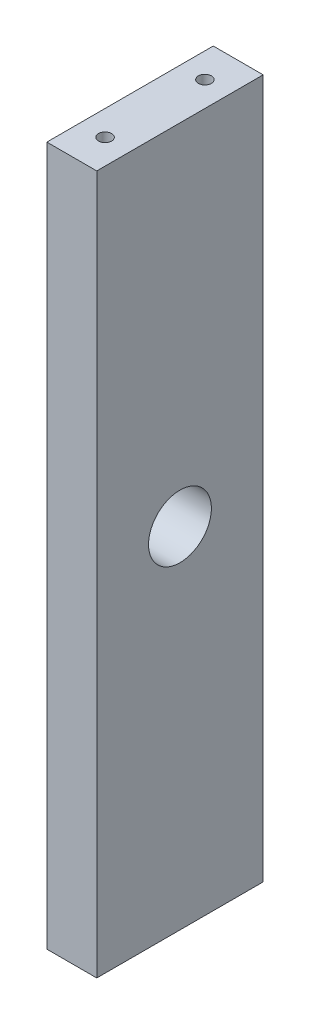
SolidWorks part; units mm, degrees
ref_plane "Front Plane" through (0, 0, 0) normal (0, 0, 1) x (1, 0, 0)
ref_plane "Top Plane" through (0, 0, 0) normal (0, 1, 0) x (1, 0, 0)
ref_plane "Right Plane" through (0, 0, 0) normal (1, 0, 0) x (0, 0, -1)
sketch "Sketch1" plane through (0, 0, 0) normal (1, 0, 0) x (0, 0, -1)
  line L1 (-15.875, -66.675) -> (15.875, -66.675)
  line L2 (-15.875, -66.675) -> (-15.875, 66.675)
  line L3 (-15.875, 66.675) -> (15.875, 66.675)
  line L4 (15.875, -66.675) -> (15.875, 66.675)
  line L5 (-15.875, -66.675) -> (15.875, 66.675) construction
  line L6 (-15.875, 66.675) -> (15.875, -66.675) construction
  point P0 (0, 0)
  dimension "D1" = 31.75
  dimension "D2" = 133.35
extrude "Boss-Extrude1" add sketch "Sketch1" along normal mid plane 9.525
sketch "Sketch2" plane through (0, 66.675, 0) normal (0, 1, 0) x (1, 0, 0)
  line L0 (0, 9.525) -> (0, -9.525) construction
  line L1 (-4.7625, 15.875) -> (-4.7625, -15.875) construction
  line L2 (4.7625, 15.875) -> (-4.7625, 15.875) construction
  point P2 (0, 0)
  point P5 (-4.7625, 0)
  point P8 (0, 15.875)
  point P10 (0, 9.525)
  point P11 (0, -9.525)
  dimension "D1" = 19.05
hole_wizard "M3x0.5 Tapped Hole1" positions "Sketch3" profile "Sketch4" tap size "M3x0.5" standard "ANSI Metric"
sketch "Sketch3" plane through (0, 66.675, 0) normal (0, 1, 0) x (1, 0, 0)
  point P0 (0, 9.525)
  point P3 (0, -9.525)
sketch "Sketch4" plane through (0, 66.675, -9.525) normal (1, 0, 0) x (0, 0, 1)
  line L0 (0, 0) -> (0, 13.4511)
  line L1 (0, 13.4511) -> (1.25, 12.7)
  line L2 (1.25, 12.7) -> (1.25, 0)
  line L5 (1.25, 0) -> (0, 0)
  line L10 (0, 13.4511) -> (-1.25, 12.7) construction
  line L11 (0, -6.35) -> (0, 107.95) construction
  dimension "Tap Drill Dia." = 2.5
  dimension "Tap Drill Depth" = 12.7
  dimension "Drill Angle" = 118
cosmetic thread "Hole Thread1" parameters "D1"=6.096, "D2"=3
cosmetic thread "Hole Thread2" parameters "D1"=6.096, "D2"=3
mirror "Mirror1" about plane through (0, 0, 0) normal (0, 1, 0) of "M3x0.5 Tapped Hole1"
cosmetic thread "Hole Thread3" parameters "D1"=6.096, "D2"=3
cosmetic thread "Hole Thread4" parameters "D1"=6.096, "D2"=3
sketch "Sketch5" plane through (4.7625, 0, 0) normal (1, 0, 0) x (0, 0, -1)
  point P0 (0, 0)
hole_wizard "Ø12.0mm Dowel Hole1" positions "Sketch6" profile "Sketch8" hole size "Ø12.0" standard "ANSI Metric" end condition through all
sketch "Sketch6" plane through (4.7625, 0, 0) normal (1, 0, 0) x (0, 0, -1)
  point P0 (0, 0)
sketch "Sketch8" plane through (4.7625, 0, 0) normal (0, 1, 0) x (0, 0, -1)
  line L0 (0, 0) -> (0, 9.525)
  line L1 (0, 9.525) -> (6, 9.525)
  line L2 (6, 9.525) -> (6, 0)
  line L5 (6, 0) -> (0, 0)
  line L11 (0, -6.35) -> (0, 107.95) construction
  dimension "Thru Hole Dia." = 12
  dimension "Thru Hole Depth" = 9.525
